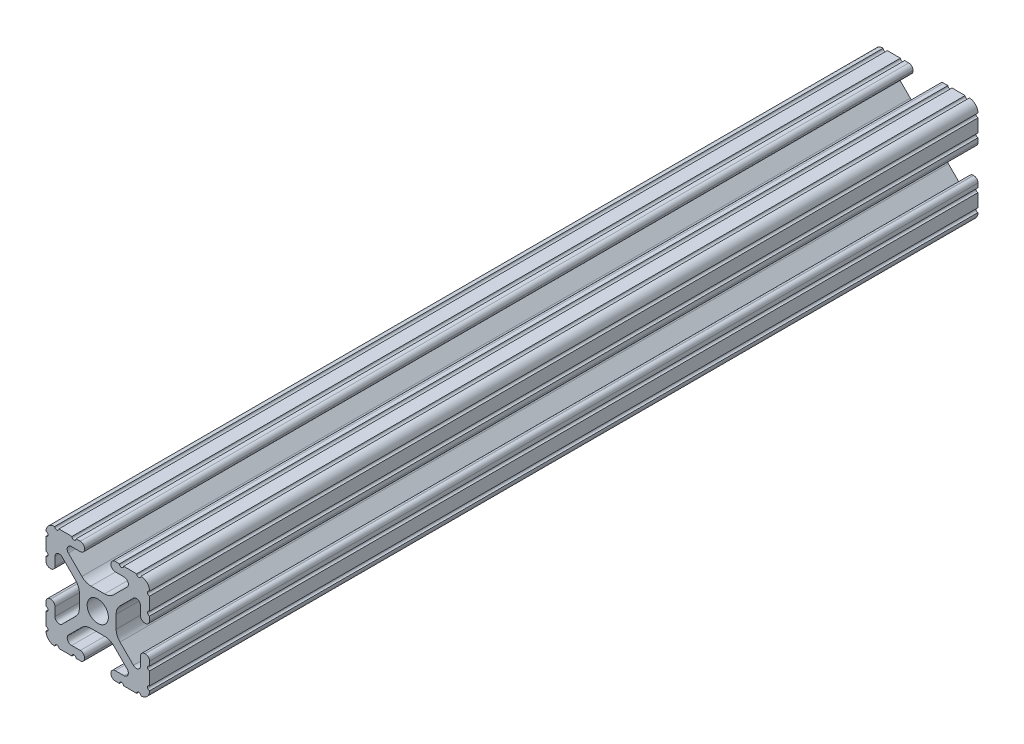
SolidWorks part; units mm, degrees
ref_plane "Front Plane" through (0, 0, 0) normal (0, 0, 1) x (1, 0, 0)
ref_plane "Top Plane" through (0, 0, 0) normal (0, 1, 0) x (1, 0, 0)
ref_plane "Right Plane" through (0, 0, 0) normal (1, 0, 0) x (0, 0, -1)
sketch "Sketch1" plane through (0, 0, 0) normal (0, 0, 1) x (1, 0, 0)
  line L0 (-7.207, 8.7244) -> (-3.8983, 5.4232)
  line L1 (-4.2875, 10.4902) -> (-6.4768, 10.4902)
  line L2 (-3.2385, 11.651) -> (-3.2385, 11.5392)
  line L3 (-5.3171, 12.7) -> (-4.2875, 12.7)
  line L4 (0, 13.4005) -> (0, -14.8534) construction
  line L5 (12.7, 0) -> (-13.9989, 0) construction
  line L6 (-9.5504, 12.7) -> (-6.3331, 12.7)
  line L7 (-12.7, 6.3331) -> (-12.7, 9.5504)
  line L8 (-12.7, 4.2875) -> (-12.7, 5.3171)
  line L9 (-11.5392, 3.2385) -> (-11.651, 3.2385)
  line L10 (-10.4902, 6.4021) -> (-10.4902, 4.2875)
  line L11 (-5.441, 3.8408) -> (-8.7371, 7.1294)
  line L12 (-4.5085, -1.5932) -> (-4.5085, 1.5932)
  line L13 (-1.7093, -4.4958) -> (1.7093, -4.4958)
  line L14 (3.9523, -5.4237) -> (7.1797, -8.6452)
  line L15 (6.4164, -10.4902) -> (4.2875, -10.4902)
  line L16 (3.2385, -11.5392) -> (3.2385, -11.651)
  line L17 (4.2875, -12.7) -> (5.3171, -12.7)
  line L18 (6.3331, -12.7) -> (9.5504, -12.7)
  line L19 (12.7, -9.5504) -> (12.7, -6.3331)
  line L20 (12.7, -5.3171) -> (12.7, -4.2875)
  line L21 (11.651, -3.2385) -> (11.5392, -3.2385)
  line L22 (10.4902, -4.2875) -> (10.4902, -6.4021)
  line L23 (8.7371, -7.1294) -> (5.441, -3.8408)
  line L24 (4.5085, -1.5932) -> (4.5085, 1.5932)
  line L25 (5.441, 3.8408) -> (8.7371, 7.1294)
  line L26 (10.4902, 6.4021) -> (10.4902, 4.2875)
  line L27 (11.5392, 3.2385) -> (11.651, 3.2385)
  line L28 (12.7, 4.2875) -> (12.7, 5.3171)
  line L29 (12.7, 6.3331) -> (12.7, 9.5504)
  line L30 (9.5504, 12.7) -> (6.3331, 12.7)
  line L31 (5.3171, 12.7) -> (4.2875, 12.7)
  line L32 (3.2385, 11.651) -> (3.2385, 11.5392)
  line L33 (4.2875, 10.4902) -> (6.4768, 10.4902)
  line L34 (7.207, 8.7244) -> (3.8983, 5.4232)
  line L35 (1.6558, 4.4958) -> (-1.6558, 4.4958)
  line L36 (-8.7371, -7.1294) -> (-5.441, -3.8408)
  line L37 (-10.4902, -4.2875) -> (-10.4902, -6.4021)
  line L38 (-11.651, -3.2385) -> (-11.5392, -3.2385)
  line L39 (-12.7, -5.3171) -> (-12.7, -4.2875)
  line L40 (-12.7, -9.5504) -> (-12.7, -6.3331)
  line L41 (-6.3331, -12.7) -> (-9.5504, -12.7)
  line L42 (-4.2875, -12.7) -> (-5.3171, -12.7)
  line L43 (-3.2385, -11.5392) -> (-3.2385, -11.651)
  line L44 (-6.4164, -10.4902) -> (-4.2875, -10.4902)
  line L45 (-3.9523, -5.4237) -> (-7.1797, -8.6452)
  arc A0 (-7.207, 8.7244) -> (-6.4768, 10.4902) centre (-6.4768, 9.4563) cw
  arc A1 (-3.2385, 11.5392) -> (-4.2875, 10.4902) centre (-4.2875, 11.5392) cw
  arc A2 (-4.2875, 12.7) -> (-3.2385, 11.651) centre (-4.2875, 11.651) cw
  arc A3 (-5.3171, 12.7) -> (-6.3331, 12.7) centre (-5.8251, 12.7) cw
  arc A4 (-9.5504, 12.7) -> (-10.5664, 12.6998) centre (-10.0584, 12.7) cw
  arc A5 (-12.6998, 10.5664) -> (-10.5664, 12.6998) centre (-10.5918, 10.5918) cw
  arc A6 (-12.6998, 10.5664) -> (-12.7, 9.5504) centre (-12.7, 10.0584) cw
  arc A7 (-12.7, 6.3331) -> (-12.7, 5.3171) centre (-12.7, 5.8251) cw
  arc A8 (-11.651, 3.2385) -> (-12.7, 4.2875) centre (-11.651, 4.2875) cw
  arc A9 (-10.4902, 4.2875) -> (-11.5392, 3.2385) centre (-11.5392, 4.2875) cw
  circle A10 centre (0, 0) radius 2.6035
  arc A11 (-10.4902, 6.4021) -> (-8.7371, 7.1294) centre (-9.4628, 6.4021) cw
  arc A12 (-5.441, 3.8408) -> (-4.5085, 1.5932) centre (-7.6835, 1.5932) cw
  arc A13 (-4.5085, -1.5932) -> (-5.441, -3.8408) centre (-7.6835, -1.5932) cw
  arc A14 (-8.7371, -7.1294) -> (-10.4902, -6.4021) centre (-9.4628, -6.4021) cw
  arc A15 (-1.7093, -4.4958) -> (-3.9523, -5.4237) centre (-1.7093, -7.6708) ccw
  arc A16 (3.9523, -5.4237) -> (1.7093, -4.4958) centre (1.7093, -7.6708) ccw
  arc A17 (6.4164, -10.4902) -> (7.1797, -8.6452) centre (6.4164, -9.4098) ccw
  arc A18 (4.2875, -10.4902) -> (3.2385, -11.5392) centre (4.2875, -11.5392) ccw
  arc A19 (3.2385, -11.651) -> (4.2875, -12.7) centre (4.2875, -11.651) ccw
  arc A20 (6.3331, -12.7) -> (5.3171, -12.7) centre (5.8251, -12.7) ccw
  arc A21 (10.5664, -12.6998) -> (9.5504, -12.7) centre (10.0584, -12.7) ccw
  arc A22 (10.5664, -12.6998) -> (12.6998, -10.5664) centre (10.5918, -10.5918) ccw
  arc A23 (12.7, -9.5504) -> (12.6998, -10.5664) centre (12.7, -10.0584) ccw
  arc A24 (12.7, -5.3171) -> (12.7, -6.3331) centre (12.7, -5.8251) ccw
  arc A25 (12.7, -4.2875) -> (11.651, -3.2385) centre (11.651, -4.2875) ccw
  arc A26 (11.5392, -3.2385) -> (10.4902, -4.2875) centre (11.5392, -4.2875) ccw
  arc A27 (8.7371, -7.1294) -> (10.4902, -6.4021) centre (9.4628, -6.4021) ccw
  arc A28 (4.5085, -1.5932) -> (5.441, -3.8408) centre (7.6835, -1.5932) ccw
  arc A29 (5.441, 3.8408) -> (4.5085, 1.5932) centre (7.6835, 1.5932) ccw
  arc A30 (10.4902, 6.4021) -> (8.7371, 7.1294) centre (9.4628, 6.4021) ccw
  arc A31 (10.4902, 4.2875) -> (11.5392, 3.2385) centre (11.5392, 4.2875) ccw
  arc A32 (11.651, 3.2385) -> (12.7, 4.2875) centre (11.651, 4.2875) ccw
  arc A33 (12.7, 6.3331) -> (12.7, 5.3171) centre (12.7, 5.8251) ccw
  arc A34 (12.6998, 10.5664) -> (12.7, 9.5504) centre (12.7, 10.0584) ccw
  arc A35 (12.6998, 10.5664) -> (10.5664, 12.6998) centre (10.5918, 10.5918) ccw
  arc A36 (9.5504, 12.7) -> (10.5664, 12.6998) centre (10.0584, 12.7) ccw
  arc A37 (5.3171, 12.7) -> (6.3331, 12.7) centre (5.8251, 12.7) ccw
  arc A38 (4.2875, 12.7) -> (3.2385, 11.651) centre (4.2875, 11.651) ccw
  arc A39 (3.2385, 11.5392) -> (4.2875, 10.4902) centre (4.2875, 11.5392) ccw
  arc A40 (7.207, 8.7244) -> (6.4768, 10.4902) centre (6.4768, 9.4563) ccw
  arc A41 (1.6558, 4.4958) -> (3.8983, 5.4232) centre (1.6558, 7.6708) ccw
  arc A42 (-1.6558, 4.4958) -> (-3.8983, 5.4232) centre (-1.6558, 7.6708) cw
  arc A43 (-11.5392, -3.2385) -> (-10.4902, -4.2875) centre (-11.5392, -4.2875) cw
  arc A44 (-12.7, -4.2875) -> (-11.651, -3.2385) centre (-11.651, -4.2875) cw
  arc A45 (-12.7, -5.3171) -> (-12.7, -6.3331) centre (-12.7, -5.8251) cw
  arc A46 (-12.7, -9.5504) -> (-12.6998, -10.5664) centre (-12.7, -10.0584) cw
  arc A47 (-10.5664, -12.6998) -> (-12.6998, -10.5664) centre (-10.5918, -10.5918) cw
  arc A48 (-10.5664, -12.6998) -> (-9.5504, -12.7) centre (-10.0584, -12.7) cw
  arc A49 (-6.3331, -12.7) -> (-5.3171, -12.7) centre (-5.8251, -12.7) cw
  arc A50 (-3.2385, -11.651) -> (-4.2875, -12.7) centre (-4.2875, -11.651) cw
  arc A51 (-4.2875, -10.4902) -> (-3.2385, -11.5392) centre (-4.2875, -11.5392) cw
  arc A52 (-6.4164, -10.4902) -> (-7.1797, -8.6452) centre (-6.4164, -9.4098) cw
  dimension "D1" = 5.207
  dimension "D9" = 14.859
  dimension "D2" = 25.4
  dimension "D3" = 12.7
  dimension "D4" = 6.477
  dimension "D5" = 8.2042
  dimension "D6" = 9.017
  dimension "D8" = 2.2098
  dimension "D10" = 2.2098
extrude "Extrude1" add sketch "Sketch1" against normal blind 203.2
